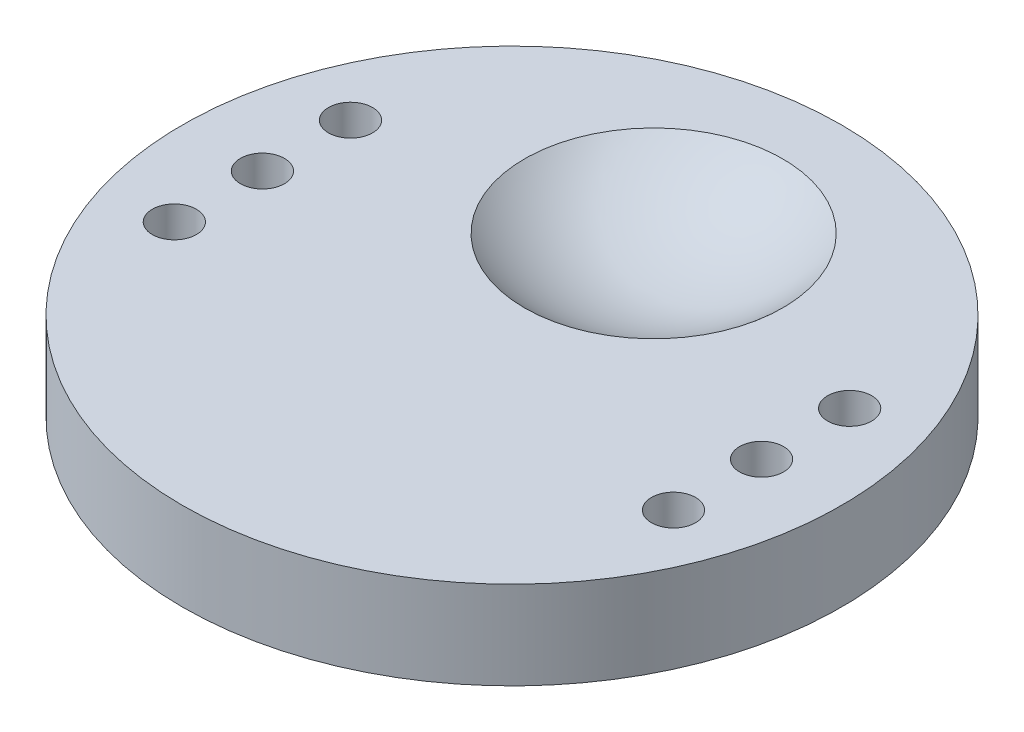
SolidWorks part; units mm, degrees
ref_plane "Front" through (0, 0, 0) normal (0, 0, 1) x (1, 0, 0)
ref_plane "Top" through (0, 0, 0) normal (0, 1, 0) x (1, 0, 0)
ref_plane "Right" through (0, 0, 0) normal (1, 0, 0) x (0, 0, -1)
sketch "Sketch1" plane through (0, 0, 0) normal (0, 1, 0) x (1, 0, 0)
  line L1 (-55, 0) -> (55, 0) construction
  line L2 (0, 0) -> (0, -13.1064) construction
  circle A0 centre (0, 0) radius 37.4142
  circle A1 centre (-28.335, 0) radius 2.5
  circle A2 centre (28.335, 0) radius 2.5
  circle A3 centre (-28.335, 10) radius 2.5
  circle A4 centre (-28.335, -10) radius 2.5
  circle A5 centre (28.335, -10) radius 2.5
  circle A6 centre (28.335, 10) radius 2.5
  dimension "D1" = 74.8284
  dimension "D3" = 5
  dimension "D2" = 28.335
extrude "Boss-Extrude1" add sketch "Sketch1" along normal blind 10 contours A0
sketch "Sketch2" plane through (0, 0, 0) normal (1, 0, 0) x (0, 0, -1)
  line L0 (37.4142, 10) -> (-37.4142, 10) construction
  line L1 (37.4142, 10) -> (30.7398, 10) construction
  line L3 (16.0792, 46.835) -> (16.0792, 4.165)
  line L4 (16.0792, 52.5336) -> (16.0792, 60.2872) construction
  line L5 (1.4394, 10) -> (-37.4142, 10) construction
  arc A0 (16.0792, 4.165) -> (16.0792, 46.835) centre (16.0792, 25.5) ccw
  dimension "D1" = 42.67
  dimension "D2" = 21.335
  dimension "D3" = 15.5
revolve "Cut-Revolve12" cut sketch "Sketch2" angle 360 about L4
